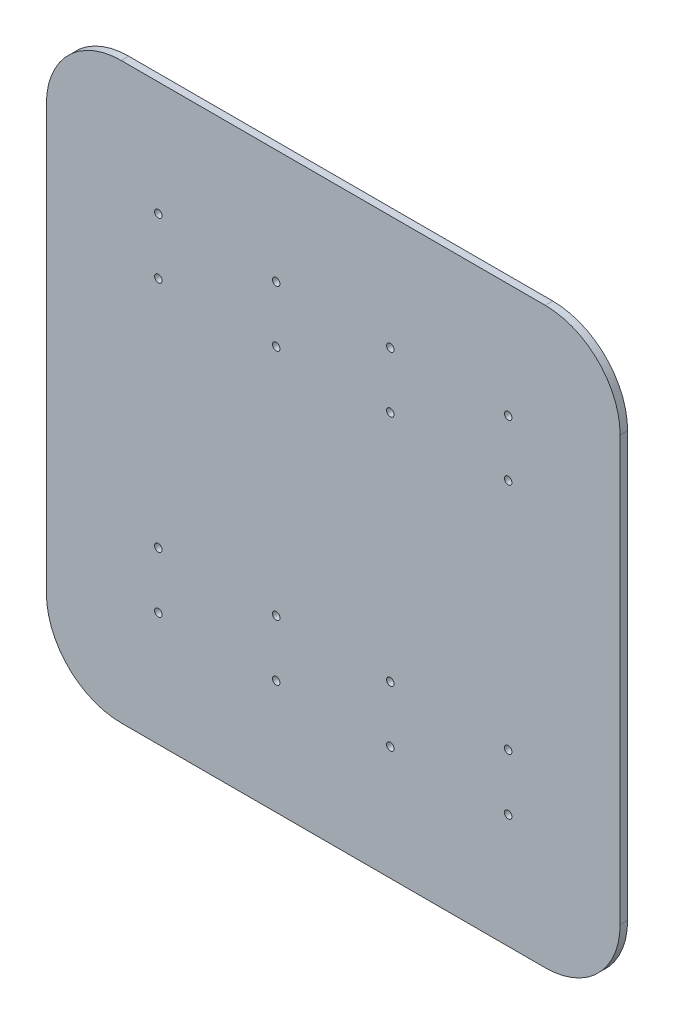
SolidWorks part; units mm, degrees
ref_plane "Alzado" through (0, 0, 0) normal (0, 0, 1) x (1, 0, 0)
ref_plane "Planta" through (0, 0, 0) normal (0, 1, 0) x (1, 0, 0)
ref_plane "Vista lateral" through (0, 0, 0) normal (1, 0, 0) x (0, 0, -1)
sketch "Croquis1" plane through (0, 0, 0) normal (0, 0, 1) x (1, 0, 0)
  line L1 (115, -115) -> (-115, -115)
  line L2 (115, -115) -> (115, 115)
  line L3 (115, 115) -> (-115, 115)
  line L4 (-115, -115) -> (-115, 115)
  line L5 (115, -115) -> (-115, 115) construction
  line L6 (115, 115) -> (-115, -115) construction
  point P0 (0, 0)
  dimension "D1" = 230
  dimension "D2" = 230
extrude "Saliente-Extruir1" add sketch "Croquis1" along normal blind 3
fillet "Redondeo1" radius 30 1 edges at (115, 115, 1.5)
fillet "Redondeo2" radius 30 1 edges at (115, -115, 1.5)
fillet "Redondeo3" radius 30 1 edges at (-115, -115, 1.5)
fillet "Redondeo4" radius 30 1 edges at (-115, 115, 1.5)
sketch "Croquis2" plane through (0, 0, 3) normal (0, 0, 1) x (1, 0, 0)
  line L0 (-115, 85) -> (-81, 85)
  line L1 (-81, 85) -> (-81, 73)
  line L2 (-81, 31) -> (-115, 31)
  line L3 (-115, 85) -> (-115, -85) construction
  line L4 (-115, 31) -> (-115, 85)
  line L5 (-115, 0) -> (115, 0) construction
  line L6 (0, 115) -> (0, -115) construction
  line L7 (85, 115) -> (-85, 115) construction
  line L8 (-85, -115) -> (85, -115) construction
  line L9 (-81, 43) -> (-81, 31)
  line L10 (-1, 43) -> (-81, 43)
  line L11 (-1, 43) -> (-1, 73)
  line L12 (-1, 73) -> (-81, 73)
  line L13 (115, -85) -> (115, 85) construction
  line L14 (-19.5, 43) -> (-81, 43)
  line L15 (-19.5, 43) -> (-19.5, 73)
  line L16 (-19.5, 73) -> (-81, 73)
  line L17 (-81, -43) -> (-81, -31)
  line L18 (-1, -43) -> (-81, -43)
  line L19 (-1, -43) -> (-1, -73)
  line L20 (-1, -73) -> (-81, -73)
  line L21 (-73.5, 43) -> (-81, 43)
  line L22 (-73.5, 43) -> (-73.5, 73)
  line L23 (-73.5, 73) -> (-81, 73)
  line L24 (-81, 43) -> (-81, 73)
  line L25 (-81, -85) -> (-81, -73)
  line L26 (-115, -85) -> (-81, -85)
  line L27 (-115, -31) -> (-115, -85)
  line L28 (-81, -31) -> (-115, -31)
  line L29 (115, -31) -> (115, -85)
  line L30 (115, -85) -> (81, -85)
  line L31 (81, -85) -> (81, -73)
  line L32 (1, -73) -> (81, -73)
  line L33 (1, -43) -> (1, -73)
  line L34 (1, -43) -> (81, -43)
  line L35 (81, -43) -> (81, -31)
  line L36 (81, -31) -> (115, -31)
  line L37 (81, 43) -> (81, 31)
  line L38 (1, 43) -> (81, 43)
  line L39 (1, 43) -> (1, 73)
  line L40 (1, 73) -> (81, 73)
  line L41 (81, 85) -> (81, 73)
  line L42 (115, 85) -> (81, 85)
  line L43 (115, 31) -> (115, 85)
  line L44 (81, 31) -> (115, 31)
  line L45 (-73.5, 43) -> (-19.5, 43) construction
  line L46 (-46.5, 43) -> (-46.5, 73) construction
  line L47 (-73.5, 58) -> (-19.5, 58) construction
  circle A0 centre (-70.125, 69.25) radius 1.5
  circle A1 centre (-22.875, 69.25) radius 1.5
  circle A2 centre (-22.875, 46.75) radius 1.5
  circle A3 centre (-70.125, 46.75) radius 1.5
  circle A4 centre (22.875, 46.75) radius 1.5
  circle A5 centre (22.875, 69.25) radius 1.5
  circle A6 centre (70.125, 46.75) radius 1.5
  circle A7 centre (70.125, 69.25) radius 1.5
  circle A8 centre (70.125, -69.25) radius 1.5
  circle A9 centre (70.125, -46.75) radius 1.5
  circle A10 centre (22.875, -69.25) radius 1.5
  circle A11 centre (22.875, -46.75) radius 1.5
  circle A12 centre (-22.875, -69.25) radius 1.5
  circle A13 centre (-22.875, -46.75) radius 1.5
  circle A14 centre (-70.125, -46.75) radius 1.5
  circle A15 centre (-70.125, -69.25) radius 1.5
  dimension "D8" = 3.375
  dimension "D10" = 3
  dimension "D1" = 34
  dimension "D2" = 54
  dimension "D3" = 30
  dimension "D4" = 80
  dimension "D5" = 54
  dimension "D6" = 18.5
  dimension "D7" = 7.5
  dimension "D9" = 3.75
extrude "Cortar-Extruir1" cut sketch "Croquis2" against normal blind 3 contours A0 | A3 | A2 | A5 | A4 | A6 | A7 | A8 | A9 | A11 | A10 | A12 | A15 | A14 | A13 | A1
sketch "Croquis3" plane through (0, 0, 3) normal (0, 0, 1) x (1, 0, 0)
  line L0 (0, 115) -> (0, -115) construction
  line L1 (-115, 0) -> (115, 0) construction
  line L2 (-115, 85) -> (-115, -85) construction
  line L3 (115, -85) -> (115, 85) construction
  line L4 (85, 115) -> (-85, 115) construction
  line L5 (-85, -115) -> (85, -115) construction
  line L6 (68.625, 69.25) -> (70.125, 69.25) construction
  line L7 (70.125, 69.25) -> (70.125, 115) construction
  line L8 (70.125, 69.25) -> (115, 69.25) construction
  circle A0 centre (70.125, 69.25) radius 1.5 construction
